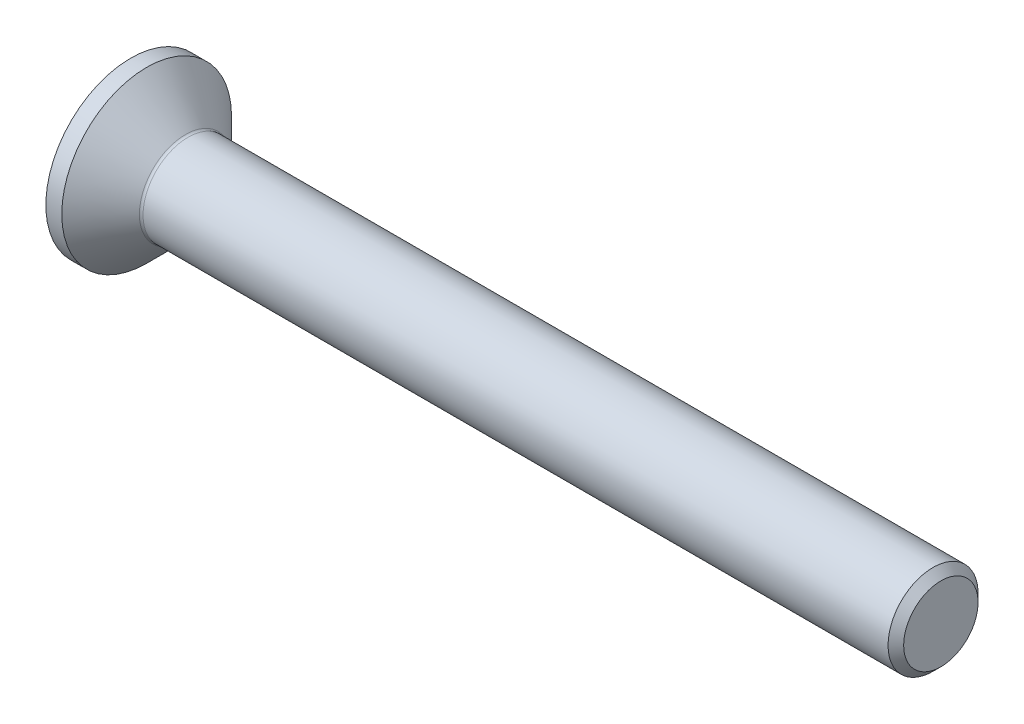
SolidWorks part; units mm, degrees
ref_plane "Front" through (0, 0, 0) normal (0, 0, 1) x (1, 0, 0)
ref_plane "Top" through (0, 0, 0) normal (0, 1, 0) x (1, 0, 0)
ref_plane "Right" through (0, 0, 0) normal (1, 0, 0) x (0, 0, -1)
sketch "Sketch1" plane through (0, 0, 0) normal (0, 0, 1) x (1, 0, 0)
  line L0 (0, 0) -> (0, 5.6)
  line L1 (0, 5.6) -> (3.1, 2.5)
  line L2 (3.1, 2.5) -> (45, 2.5)
  line L3 (45, 2.5) -> (45, 0)
  line L4 (45, 0) -> (0, 0)
  line L5 (-0.5871, 0) -> (5.4927, 0) construction
  dimension "l" = 45
  dimension "k" = 3.1
  dimension "d" = 5
  dimension "D1" = 45
revolve "Base" add sketch "Sketch1" angle 360 about L5
cosmetic thread "ThreadCosmetic1" parameters "b"=22, "D2"=4.134
sketch "Sketch2" plane through (0, 0, 0) normal (1, 0, 0) x (0, 0, -1)
  line L1 (1.7321, 0) -> (0.866, 1.5)
  line L2 (0.866, 1.5) -> (-0.866, 1.5)
  line L3 (-0.866, 1.5) -> (-1.7321, 0)
  line L4 (-1.7321, 0) -> (-0.866, -1.5)
  line L5 (-0.866, -1.5) -> (0.866, -1.5)
  line L6 (0.866, -1.5) -> (1.7321, 0)
  circle A0 centre (0, 0) radius 1.5 construction
  dimension "s" = 3
extrude "HexagonSocket" cut sketch "Sketch2" along normal blind 1.9
sketch "Sketch3" plane through (0, 0, 0) normal (0, 0, 1) x (1, 0, 0)
  line L0 (-0.4391, 0) -> (4.425, 0) construction
  line L1 (1.9, 0) -> (1.9, -1.5) construction
  line L2 (1.9, 1.5) -> (2.766, 0)
  line L3 (2.766, 0) -> (1.9, -1.5) construction
  line L4 (1.9, 1.5) -> (1.9, 0)
  line L5 (1.9, 0) -> (2.766, 0)
  line L7 (1.9, 1.5) -> (1.9, 0) construction
  dimension "D1" = 120
revolve "Cut-Revolve1" cut sketch "Sketch3" angle 360 about L0
fillet "HeadFillet" radius 0.2 1 edges at (3.1, 0, 2.5)
chamfer "Chamfer" distance 0.433 angle 45 1 edges at (45, 0, 2.5)
sketch "Sketch4" plane through (0, 0, 0) normal (0, 1, 0) x (1, 0, 0)
  line L0 (11.8531, 0) -> (-2.694, 0) construction
  line L1 (-2, 9.715) -> (3, 9.715)
  line L2 (-2, 9.715) -> (-2, 4.715)
  line L3 (-2, 4.715) -> (3, 4.715)
  line L4 (3, 9.715) -> (3, 4.715)
  line L5 (0, 5.6) -> (0, -5.6) construction
  dimension "dk" = 9.43
  dimension "D2" = 2
  dimension "D3" = 5
  dimension "D4" = 5
revolve "Cut-Revolve2" cut sketch "Sketch4" angle 360 about L0
sketch "Sketch5" plane through (0, 0, 0) normal (0, 0, 1) x (1, 0, 0)
  line L0 (44.567, 2.125) -> (44.7835, 2.5)
  line L1 (44.7835, 2.5) -> (44.7835, 2.933)
  line L2 (44.7835, 2.933) -> (44.3505, 2.933)
  line L3 (44.3505, 2.933) -> (44.3505, 2.5)
  line L4 (44.3505, 2.5) -> (44.567, 2.125)
  line L5 (0, 0) -> (10.6885, 0) construction
  line L6 (44.567, 2.5) -> (44.567, -2.5) construction
  dimension "D1" = 5
  dimension "D2" = 0.433
revolve "Cut-Revolve10" [suppressed] cut sketch "Sketch5" angle 360 about L5
pattern_linear "LPattern10" [suppressed] count 42 spacing 0.5196 along (1, 0, 0)
equation "\"D1@Chamfer\" = (  \"d@Sketch1\" - \"D2@ThreadCosmetic1\" )  / 2"
equation "\"D1@Sketch5\" = \"d@Sketch1\""
equation "\"D2@Sketch5\" =  ( \"d@Sketch1\" - \"D2@ThreadCosmetic1\" )  / 2"
equation "\"D3@LPattern10\" = \"D2@Sketch5\" * 1.2"
equation "\"D1@LPattern10\" = \"b@ThreadCosmetic1\" / \"D3@LPattern10\""
